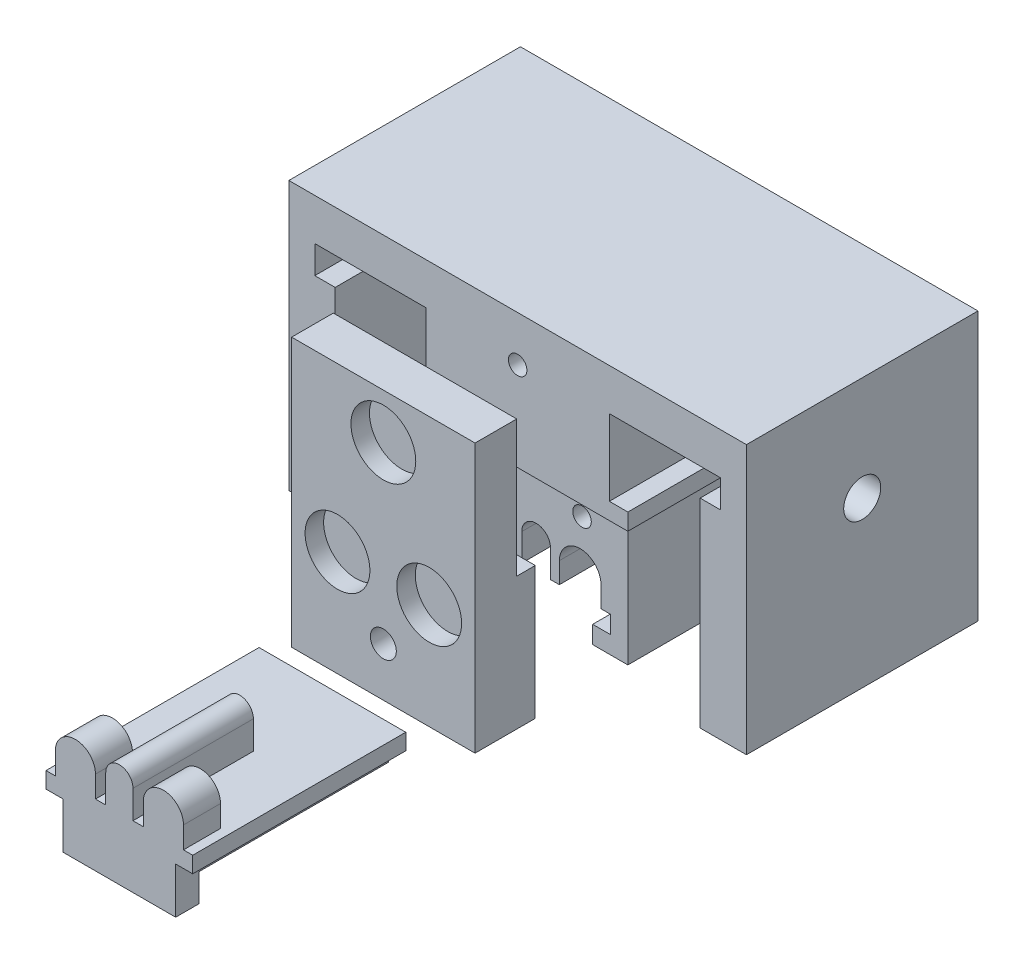
SolidWorks part; units mm, degrees
ref_plane "Front Plane" through (0, 0, 0) normal (0, 0, 1) x (1, 0, 0)
ref_plane "Top Plane" through (0, 0, 0) normal (0, 1, 0) x (1, 0, 0)
ref_plane "Right Plane" through (0, 0, 0) normal (1, 0, 0) x (0, 0, -1)
sketch "Sketch1" plane through (0, 0, 0) normal (0, 0, 1) x (1, 0, 0)
  line L0 (-21.9, 7) -> (-21.9, 10)
  line L1 (-21.9, 10) -> (-9.9, 10)
  line L2 (-9.9, 10) -> (-9.9, 1.8)
  line L3 (-9.9, -14.5) -> (9.9, -14.5)
  line L4 (9.9, -14.5) -> (9.9, 0)
  line L5 (9.9, 10) -> (21.9, 10)
  line L6 (21.9, 10) -> (21.9, 7)
  line L7 (19.7, -14.5) -> (24.7, -14.5)
  line L8 (24.7, -14.5) -> (24.7, 14.5)
  line L9 (24.7, 14.5) -> (-24.7, 14.5)
  line L14 (-24.7, 14.5) -> (-24.7, -14.5)
  line L16 (-21.9, 7) -> (-19.7, 7)
  line L17 (-19.7, 7) -> (-19.7, -14.5)
  line L18 (-19.7, -14.5) -> (-24.7, -14.5)
  line L19 (21.9, 7) -> (19.7, 7)
  line L20 (19.7, 7) -> (19.7, -14.5)
  line L22 (-9.9, 1.8) -> (-11.9, 1.8)
  line L23 (-11.9, 1.8) -> (-11.9, 0)
  line L24 (-11.9, 0) -> (-9.9, 0)
  line L25 (9.9, 1.8) -> (11.9, 1.8)
  line L26 (11.9, 1.8) -> (11.9, 0)
  line L27 (11.9, 0) -> (9.9, 0)
  line L28 (-9.9, 0) -> (-9.9, -14.5)
  line L29 (9.9, 1.8) -> (9.9, 10)
  point P9 (-24.7, 0)
  point P29 (0, -14.5)
  dimension "D1" = 19.8
  dimension "D2" = 12
  dimension "D3" = 4.5
  dimension "D4" = 4.5
  dimension "D5" = 24.5
  dimension "D6" = 5
  dimension "D7" = 2.2
  dimension "D8" = 1.8
  dimension "D9" = 14.5
  dimension "D10" = 3
  dimension "D11" = 2
extrude "Boss-Extrude1" add sketch "Sketch1" along normal blind 25
sketch "Sketch2" plane through (-24.7, 0, 0) normal (-1, 0, 0) x (0, 0, 1)
  line L0 (25, 1.8) -> (0, 1.8) construction
  line L2 (25, 1.8) -> (0, 1.8) construction
  line L3 (9.1108, 1.25) -> (17.7065, 1.25) construction
  circle A0 centre (12.5, 3.25) radius 2
  point P3 (12.5, 1.8)
  dimension "D1" = 4
  dimension "D2" = 0.55
extrude "Cut-Extrude1" cut sketch "Sketch2" against normal through all
sketch "Sketch5" plane through (0, 0, 0) normal (1, 0, 0) x (0, 0, -1)
  line L1 (-8.4008, 3.25) -> (-10.4504, 6.8)
  line L2 (-10.4504, 6.8) -> (-14.5496, 6.8)
  line L3 (-14.5496, 6.8) -> (-16.5992, 3.25)
  line L4 (-16.5992, 3.25) -> (-14.5496, -0.3)
  line L5 (-14.5496, -0.3) -> (-10.4504, -0.3)
  line L6 (-10.4504, -0.3) -> (-8.4008, 3.25)
  circle A2 centre (-12.5, 3.25) radius 3.55 construction
  dimension "D1" = 7.1
extrude "Cut-Extrude2" cut sketch "Sketch5" against normal blind 6 and the other way blind 6
sketch "Sketch6" plane through (0, 0, 0) normal (0, 0, 1) x (1, 0, 0)
  line L0 (6, 6.8) -> (-6, 6.8) construction
  line L1 (3, 6.8) -> (-3, 6.8)
  line L2 (3, 6.8) -> (3, -0.3)
  line L3 (3, -0.3) -> (-3, -0.3)
  line L4 (-3, 6.8) -> (-3, -0.3)
  line L5 (6, -0.3) -> (-6, -0.3) construction
  point P9 (0, -0.3)
  dimension "D1" = 6
extrude "Cut-Extrude3" cut sketch "Sketch6" along normal up to vertex
sketch "Sketch9" plane through (0, 0, 25) normal (0, 0, 1) x (1, 0, 0)
  line L2 (-6.1, -14.5) -> (6.1, -14.5)
  line L4 (-9.9, -14.5) -> (9.9, -14.5) construction
  line L5 (6.1, -14.5) -> (6.1, -12.6)
  line L6 (6.1, -12.6) -> (8, -12.6)
  line L7 (8, -12.6) -> (8, -10.7)
  line L8 (8, -10.7) -> (-8, -10.7)
  line L9 (-8, -10.7) -> (-8, -12.6)
  line L10 (-8, -12.6) -> (-6.1, -12.6)
  line L11 (-6.1, -12.6) -> (-6.1, -14.5)
  line L12 (-9.9, 0) -> (-9.9, -14.5) construction
  line L14 (-9.9, -12.6) -> (-8, -12.6) construction
  point P12 (0, -10.7)
  dimension "D1" = 1.9
extrude "Cut-Extrude4" cut sketch "Sketch9" against normal up to next
sketch "Sketch11" plane through (0, 0, 25) normal (0, 0, 1) x (1, 0, 0)
  line L0 (-8, -10.7) -> (-8, -12.6) construction
  line L2 (8, -12.6) -> (8, -10.7) construction
  line L3 (-7, -8.45) -> (-7, -10.7)
  line L4 (-2.5, -8.45) -> (-2.5, -10.7)
  line L5 (2.5, -8.45) -> (2.5, -10.7)
  line L6 (7, -8.45) -> (7, -10.7)
  line L7 (-7, -10.7) -> (-2.5, -10.7)
  line L8 (2.5, -10.7) -> (7, -10.7)
  line L9 (-4.75, -8.45) -> (-4.75, -6.2) construction
  line L10 (8, -10.7) -> (-8, -10.7) construction
  line L12 (-1.55, -7.75) -> (-1.55, -10.7)
  line L13 (-1.55, -10.7) -> (1.55, -10.7)
  line L14 (1.55, -7.75) -> (1.55, -10.7)
  arc A0 (-2.5, -8.45) -> (-7, -8.45) centre (-4.75, -8.45) ccw
  arc A1 (7, -8.45) -> (2.5, -8.45) centre (4.75, -8.45) ccw
  arc A2 (-1.55, -7.75) -> (1.55, -7.75) centre (0, -7.75) cw
  point P22 (0, -6.2)
  point P23 (4.75, -6.2)
  dimension "D1" = 4.5
  dimension "D2" = 1
  dimension "D3" = 1
  dimension "D4" = 3.1
extrude "Cut-Extrude5" cut sketch "Sketch11" against normal blind 23
sketch "Sketch12" plane through (0, 0, 25) normal (0, 0, 1) x (1, 0, 0)
  line L0 (6.1, -14.5) -> (9.9, -14.5) construction
  line L1 (-9.9, 0) -> (9.9, 0)
  line L2 (-9.9, 0) -> (-9.9, -14.5)
  line L3 (-9.9, -14.5) -> (9.9, -14.5)
  line L4 (9.9, 0) -> (9.9, -14.5)
  line L5 (-9.9, 0) -> (9.9, -14.5) construction
  line L6 (-9.9, -14.5) -> (9.9, 0) construction
  line L7 (-9.9, 0) -> (-9.9, -14.5) construction
  line L8 (9.9, -14.5) -> (9.9, 0) construction
  line L9 (9.9, 0) -> (11.9, 0) construction
  point P0 (0, -7.25)
extrude "Cut-Extrude6" cut sketch "Sketch12" against normal blind 2
sketch "Sketch13" plane through (0, 0, 23) normal (0, 0, 1) x (1, 0, 0)
  line L0 (0, 0) -> (0, -6.2) construction
  line L1 (9.9, 0) -> (-9.9, 0) construction
  line L2 (-9.9, -3.1) -> (0, -3.1) construction
  line L5 (-9.9, 0) -> (-9.9, -14.5) construction
  line L6 (0, -3.1) -> (9.9, -3.1) construction
  line L7 (9.9, -14.5) -> (9.9, 0) construction
  line L9 (6, 6.8) -> (-6, 6.8) construction
  line L10 (6, 6.8) -> (-6, 6.8) construction
  line L11 (6, -0.3) -> (-6, -0.3) construction
  line L12 (6, -0.3) -> (-6, -0.3) construction
  line L13 (-4.95, -3.1) -> (-4.95, -0.3) construction
  line L14 (0, 9.6) -> (0, 6.8) construction
  circle A0 centre (-4.95, -3.1) radius 1
  circle A1 centre (4.95, -3.1) radius 1
  arc A2 (1.55, -7.75) -> (-1.55, -7.75) centre (0, -7.75) ccw construction
  circle A3 centre (0, 9.6) radius 1
  point P15 (0, -3.1)
  point P20 (-4.95, -3.1)
  point P21 (4.95, -3.1)
  dimension "D1" = 2
extrude "Cut-Extrude7" cut sketch "Sketch13" against normal blind 12 and the other way blind 2
ref_plane "Plane1" through (0, 0, 35) normal (0, 0, 1) x (1, 0, 0)
sketch "Sketch14" plane through (0, 0, 35) normal (0, 0, 1) x (1, 0, 0)
  line L8 (-9.9, 14.5) -> (-9.9, -14.5)
  line L9 (-9.9, -14.5) -> (9.9, -14.5)
  line L10 (9.9, -14.5) -> (9.9, 14.5)
  line L11 (24.7, 14.5) -> (-24.7, 14.5) construction
  line L12 (9.9, 14.5) -> (-9.9, 14.5)
  circle A6 centre (0, 9.6) radius 1.25
  circle A7 centre (-4.95, -3.1) radius 1.25
  circle A8 centre (4.95, -3.1) radius 1.25
  dimension "D1" = 2.5
extrude "Boss-Extrude2" add sketch "Sketch14" along normal blind 4.5 separate body
sketch "Sketch15" plane through (0, 0, 35) normal (0, 0, -1) x (-1, 0, 0)
  line L0 (9.9, -0.2) -> (-9.9, -0.2)
  line L1 (9.9, 14.5) -> (9.9, -14.5) construction
  line L2 (11.9, 0) -> (-11.9, 0) construction
  line L4 (-9.9, -14.5) -> (-9.9, 14.5) construction
  line L5 (-9.9, -0.2) -> (-9.9, -14.5)
  line L6 (-9.9, -14.5) -> (9.9, -14.5)
  line L7 (9.9, -14.5) -> (9.9, -0.2)
  circle A0 centre (4.95, -3.1) radius 1.25 construction
  circle A1 centre (-4.95, -3.1) radius 1.25 construction
  circle A2 centre (4.95, -3.1) radius 1.25
  circle A3 centre (-4.95, -3.1) radius 1.25
  dimension "D1" = 0.2
extrude "Boss-Extrude3" add sketch "Sketch15" along normal blind 2
sketch "Sketch16" plane through (0, 0, 39.5) normal (0, 0, 1) x (1, 0, 0)
  circle A0 centre (4.95, -3.1) radius 3.5
  circle A1 centre (-4.95, -3.1) radius 3.5
  circle A2 centre (0, 9.6) radius 3.5
  dimension "D1" = 7
extrude "Cut-Extrude8" cut sketch "Sketch16" against normal blind 2
sketch "Sketch17" plane through (0, 0, 37.5) normal (0, 0, 1) x (1, 0, 0)
  circle A0 centre (0, 9.6) radius 1.25 construction
  circle A1 centre (-4.95, -3.1) radius 1.25 construction
  circle A2 centre (4.95, -3.1) radius 1.25 construction
  circle A3 centre (0, 9.6) radius 1.25
  circle A4 centre (-4.95, -3.1) radius 1.25
  circle A5 centre (4.95, -3.1) radius 1.25
extrude "Boss-Extrude4" add sketch "Sketch17" against normal blind 0.6
sketch "Sketch18" plane through (0, 0, 33) normal (0, 0, -1) x (-1, 0, 0)
  line L1 (-3.1754, -9.225) -> (-1.5877, -11.975)
  line L2 (-1.5877, -11.975) -> (1.5877, -11.975)
  line L3 (1.5877, -11.975) -> (3.1754, -9.225)
  line L4 (3.1754, -9.225) -> (1.5877, -6.475)
  line L5 (1.5877, -6.475) -> (-1.5877, -6.475)
  line L6 (-1.5877, -6.475) -> (-3.1754, -9.225)
  line L7 (1.55, -10.7) -> (1.55, -7.75) construction
  circle A1 centre (0, -9.225) radius 2.75 construction
  point P14 (1.55, -9.225)
  dimension "D1" = 5.5
extrude "Cut-Extrude9" cut sketch "Sketch18" against normal blind 2.6
sketch "Sketch19" plane through (0, 0, 35.6) normal (0, 0, -1) x (-1, 0, 0)
  line L0 (1.5877, -6.475) -> (-1.5877, -6.475) construction
  circle A0 centre (0, -9.225) radius 1.4
  point P5 (0, -6.475)
  dimension "D1" = 2.8
extrude "Cut-Extrude10" cut sketch "Sketch19" against normal up to next (3.9 mm away)
ref_plane "Plane2" through (0, 0, 45) normal (0, 0, 1) x (1, 0, 0)
sketch "Sketch20" plane through (0, 0, 45) normal (0, 0, 1) x (1, 0, 0)
  line L0 (-1.55, -10.7) -> (-1.55, -7.75) construction
  line L1 (7, -8.45) -> (7, -10.7) construction
  line L2 (-2.5, -8.45) -> (-2.5, -10.7) construction
  line L3 (-6.08, -12.52) -> (-7.92, -12.52)
  line L4 (-7.92, -12.52) -> (-7.92, -10.78)
  line L5 (-6.1, -12.6) -> (-8, -12.6) construction
  line L6 (-8, -12.6) -> (-8, -10.7) construction
  line L7 (-8, -10.7) -> (-7, -10.7) construction
  line L8 (1.55, -10.7) -> (2.5, -10.7) construction
  line L9 (-2.5, -10.7) -> (-1.55, -10.7) construction
  line L10 (-7, -10.7) -> (-7, -8.45) construction
  line L11 (-7.92, -10.78) -> (-6.92, -10.78)
  line L12 (-6.92, -10.78) -> (-6.92, -8.45)
  line L13 (8, -12.6) -> (6.1, -12.6) construction
  line L14 (8, -10.7) -> (8, -12.6) construction
  line L15 (7, -10.7) -> (8, -10.7) construction
  line L16 (2.5, -10.7) -> (2.5, -8.45) construction
  line L17 (1.55, -7.75) -> (1.55, -10.7) construction
  line L18 (-2.58, -8.45) -> (-2.58, -10.78)
  line L19 (-2.58, -10.78) -> (-1.47, -10.78)
  line L20 (-6.1, -12.6) -> (-8, -12.6) construction
  line L21 (-8, -12.6) -> (-8, -10.7) construction
  line L22 (-8, -10.7) -> (-7, -10.7) construction
  line L23 (1.55, -10.7) -> (2.5, -10.7) construction
  line L24 (-2.5, -10.7) -> (-1.55, -10.7) construction
  line L25 (-7, -10.7) -> (-7, -8.45) construction
  line L26 (-1.47, -10.78) -> (-1.47, -7.75)
  line L27 (1.47, -7.75) -> (1.47, -10.78)
  line L28 (8, -12.6) -> (6.1, -12.6) construction
  line L29 (8, -10.7) -> (8, -12.6) construction
  line L30 (7, -10.7) -> (8, -10.7) construction
  line L31 (2.5, -10.7) -> (2.5, -8.45) construction
  line L32 (1.55, -7.75) -> (1.55, -10.7) construction
  line L33 (-1.55, -10.7) -> (-1.55, -7.75) construction
  line L34 (-2.5, -8.45) -> (-2.5, -10.7) construction
  line L35 (7, -8.45) -> (7, -10.7) construction
  line L36 (1.47, -10.78) -> (2.58, -10.78)
  line L37 (2.58, -10.78) -> (2.58, -8.45)
  line L38 (6.92, -8.45) -> (6.92, -10.78)
  line L39 (6.92, -10.78) -> (7.92, -10.78)
  line L40 (7.92, -10.78) -> (7.92, -12.52)
  line L41 (7.92, -12.52) -> (6.08, -12.52)
  line L42 (-6.08, -12.52) -> (-6.08, -14.5)
  line L43 (-6.08, -14.5) -> (6.08, -14.5)
  line L44 (6.08, -14.5) -> (6.08, -12.52)
  line L45 (7.92, -12.52) -> (6.1, -12.52) construction
  line L46 (-6.1, -12.52) -> (-7.92, -12.52) construction
  line L47 (-9.9, -14.5) -> (-6.1, -14.5) construction
  line L48 (-6.1, -14.5) -> (-6.1, -12.6) construction
  line L49 (6.1, -12.6) -> (6.1, -14.5) construction
  arc A0 (7, -8.45) -> (2.5, -8.45) centre (4.75, -8.45) ccw construction
  arc A1 (1.55, -7.75) -> (-1.55, -7.75) centre (0, -7.75) ccw construction
  arc A2 (-2.5, -8.45) -> (-7, -8.45) centre (-4.75, -8.45) ccw construction
  arc A3 (-2.5, -8.45) -> (-7, -8.45) centre (-4.75, -8.45) ccw construction
  arc A4 (1.55, -7.75) -> (-1.55, -7.75) centre (0, -7.75) ccw construction
  arc A5 (7, -8.45) -> (2.5, -8.45) centre (4.75, -8.45) ccw construction
  arc A6 (-2.58, -8.45) -> (-6.92, -8.45) centre (-4.75, -8.45) ccw
  arc A7 (1.47, -7.75) -> (-1.47, -7.75) centre (0, -7.75) ccw
  arc A8 (6.92, -8.45) -> (2.58, -8.45) centre (4.75, -8.45) ccw
  point P2 (-1.55, -9.225)
  point P46 (5.834, -12.52)
  dimension "D1" = 0.08
  dimension "D2" = 0.02
  dimension "D3" = 0.02
extrude "Boss-Extrude5" add sketch "Sketch20" along normal blind 23 separate body
sketch "Sketch21" plane through (0, -14.5, 0) normal (0, -1, 0) x (1, 0, 0)
  line L0 (-6.08, 68) -> (6.08, 68)
  line L1 (6.08, 68) -> (6.08, 65.5)
  line L2 (6.08, 68) -> (6.08, 45) construction
  line L3 (6.08, 65.5) -> (-6.08, 65.5)
  line L4 (-6.08, 68) -> (-6.08, 45) construction
  line L5 (-6.08, 65.5) -> (-6.08, 68)
  dimension "D1" = 2.5
extrude "Boss-Extrude6" add sketch "Sketch21" along normal blind 3
sketch "Sketch22" plane through (0, 0, 45) normal (0, 0, -1) x (-1, 0, 0)
  line L17 (7.92, -12.52) -> (7.92, -10.78)
  line L18 (7.92, -10.78) -> (6.92, -10.78)
  line L19 (6.92, -10.78) -> (6.92, -8.45)
  line L20 (2.58, -8.45) -> (2.58, -10.78)
  line L21 (2.58, -10.78) -> (1.47, -10.78)
  line L22 (1.47, -10.78) -> (1.47, -7.75)
  line L23 (-1.47, -7.75) -> (-1.47, -10.78)
  line L24 (-1.47, -10.78) -> (-2.58, -10.78)
  line L25 (-2.58, -10.78) -> (-2.58, -8.45)
  line L26 (-6.92, -8.45) -> (-6.92, -10.78)
  line L27 (-6.92, -10.78) -> (-7.92, -10.78)
  line L28 (-7.92, -10.78) -> (-7.92, -12.52)
  line L29 (-7.92, -12.52) -> (-6.08, -12.52)
  line L30 (-6.08, -12.52) -> (-6.08, -14.5)
  line L31 (-6.08, -14.5) -> (6.08, -14.5)
  line L32 (6.08, -14.5) -> (6.08, -12.52)
  line L33 (6.08, -12.52) -> (7.92, -12.52)
  line L36 (6.92, -10.78) -> (6.92, -8.45)
  line L37 (2.58, -8.45) -> (2.58, -10.78)
  line L38 (6.92, -10.78) -> (-1.47, -10.78)
  line L39 (1.47, -10.78) -> (1.47, -7.75)
  line L40 (-1.47, -7.75) -> (-1.47, -10.78)
  line L41 (-1.47, -10.78) -> (-6.92, -10.78)
  line L42 (-2.58, -10.78) -> (-2.58, -8.45)
  line L43 (-6.92, -8.45) -> (-6.92, -10.78)
  arc A3 (6.92, -8.45) -> (2.58, -8.45) centre (4.75, -8.45) ccw
  arc A4 (1.47, -7.75) -> (-1.47, -7.75) centre (0, -7.75) ccw
  arc A5 (-2.58, -8.45) -> (-6.92, -8.45) centre (-4.75, -8.45) ccw
  arc A6 (6.92, -8.45) -> (2.58, -8.45) centre (4.75, -8.45) ccw
  arc A7 (1.47, -7.75) -> (-1.47, -7.75) centre (0, -7.75) ccw
  arc A8 (-2.58, -8.45) -> (-6.92, -8.45) centre (-4.75, -8.45) ccw
  line M23 (6.92, -10.78) -> (6.92, -8.45)
  arc M24 (6.92, -8.45) -> (2.58, -8.45) centre (4.75, -8.45) ccw
  line M25 (2.58, -8.45) -> (2.58, -10.78)
  line M27 (1.47, -10.78) -> (1.47, -7.75)
  arc M28 (1.47, -7.75) -> (-1.47, -7.75) centre (0, -7.75) ccw
  line M29 (-1.47, -7.75) -> (-1.47, -10.78)
  line M31 (-2.58, -10.78) -> (-2.58, -8.45)
  arc M32 (-2.58, -8.45) -> (-6.92, -8.45) centre (-4.75, -8.45) ccw
  line M33 (-6.92, -8.45) -> (-6.92, -10.78)
  dimension "D1" = 0
extrude "Cut-Extrude11" cut sketch "Sketch22" against normal blind 10 contours L38 M23 M24 M25 | L38 M27 M28 M29 | L41 M31 M32 M33
sketch "Sketch23" plane through (0, 0, 55) normal (0, 0, -1) x (-1, 0, 0)
  line L3 (-6.92, -10.78) -> (-2.58, -10.78)
  line L4 (-2.58, -10.78) -> (-2.58, -8.45)
  line L5 (-6.92, -8.45) -> (-6.92, -10.78)
  line L6 (-6.92, -10.78) -> (-2.58, -10.78)
  line L7 (-2.58, -10.78) -> (-2.58, -8.45)
  line L8 (-6.92, -8.45) -> (-6.92, -10.78)
  line L9 (2.58, -10.78) -> (6.92, -10.78)
  line L10 (6.92, -10.78) -> (6.92, -8.45)
  line L11 (2.58, -8.45) -> (2.58, -10.78)
  line L12 (2.58, -10.78) -> (6.92, -10.78)
  line L13 (6.92, -10.78) -> (6.92, -8.45)
  line L14 (2.58, -8.45) -> (2.58, -10.78)
  arc A1 (-2.58, -8.45) -> (-6.92, -8.45) centre (-4.75, -8.45) ccw
  arc A2 (-2.58, -8.45) -> (-6.92, -8.45) centre (-4.75, -8.45) ccw
  arc A3 (6.92, -8.45) -> (2.58, -8.45) centre (4.75, -8.45) ccw
  arc A4 (6.92, -8.45) -> (2.58, -8.45) centre (4.75, -8.45) ccw
  dimension "D1" = 0
  dimension "D2" = 0
extrude "Cut-Extrude12" cut sketch "Sketch23" against normal blind 9
